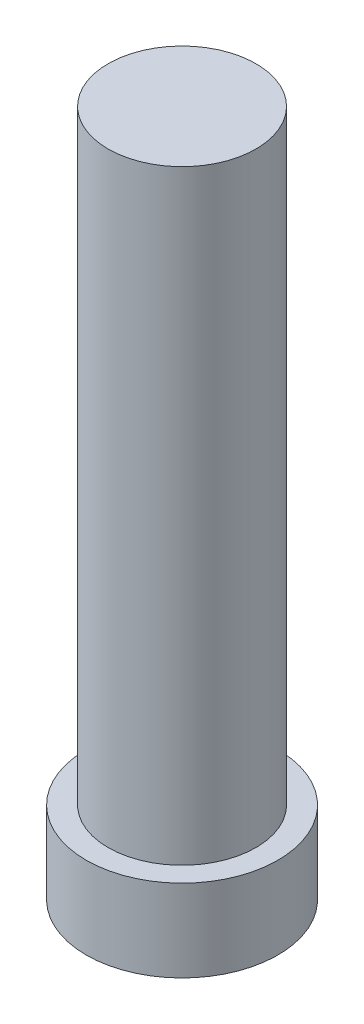
SolidWorks part; units mm, degrees
ref_plane "Front Plane" through (0, 0, 0) normal (0, 0, 1) x (1, 0, 0)
ref_plane "Top Plane" through (0, 0, 0) normal (0, 1, 0) x (1, 0, 0)
ref_plane "Right Plane" through (0, 0, 0) normal (1, 0, 0) x (0, 0, -1)
sketch "Sketch2" plane through (0, 0, 0) normal (0, 1, 0) x (1, 0, 0)
  circle A0 centre (0, 0) radius 3.5
  dimension "D1" = 7
extrude "Boss-Extrude1" add sketch "Sketch2" along normal blind 3
sketch "Sketch3" plane through (0, 3, 0) normal (0, 1, 0) x (1, 0, 0)
  circle A0 centre (0, 0) radius 2.7
  dimension "D1" = 5.4
extrude "Boss-Extrude2" add sketch "Sketch3" along normal blind 22.1
